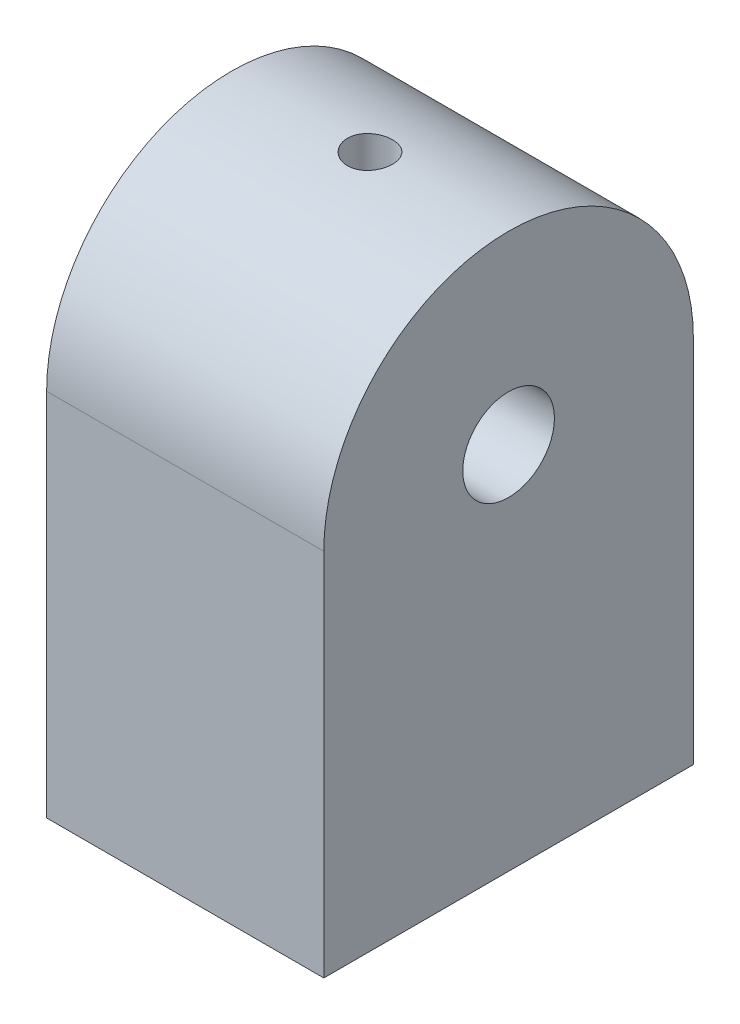
SolidWorks part; units mm, degrees
ref_plane "Front Plane" through (0, 0, 0) normal (0, 0, 1) x (1, 0, 0)
ref_plane "Top Plane" through (0, 0, 0) normal (0, 1, 0) x (1, 0, 0)
ref_plane "Right Plane" through (0, 0, 0) normal (1, 0, 0) x (0, 0, -1)
sketch "Sketch1" plane through (0, 0, 0) normal (1, 0, 0) x (0, 0, -1)
  circle A0 centre (0, 0) radius 3.15
  circle A1 centre (0, 0) radius 12.7
  point P5 (0, 0.2014)
  dimension "D1" = 6.3
  dimension "D2" = 25.4
extrude "Boss-Extrude1" add sketch "Sketch1" along normal blind 19.05
sketch "Sketch2" plane through (19.05, 0, 0) normal (1, 0, 0) x (0, 0, -1)
  line L0 (12.7, 0) -> (12.7, -25.4)
  line L1 (-12.7, 0) -> (-12.7, -25.4)
  line L2 (12.7, -25.4) -> (-12.7, -25.4)
  circle A0 centre (0, 0) radius 12.7 construction
  circle A1 centre (0, 0) radius 12.7
  circle A2 centre (0, 0) radius 12.7
  circle M4 centre (0, 0) radius 12.7
  dimension "D2" = 25.4
  dimension "D1" = 0
extrude "Boss-Extrude2" add sketch "Sketch2" against normal up to surface (19.05 mm away) contours L0 L2 L1 M4 up to face at (0, 0, -12.7)
ref_plane "Plane1" through (0, 12.7, 0) normal (0, 1, 0) x (1, 0, 0)
sketch "Sketch3" plane through (0, 12.7, 0) normal (0, 1, 0) x (1, 0, 0)
  line L0 (0, 12.7) -> (0, -12.7) construction
  line L1 (0, 12.7) -> (0, -12.7)
  line L2 (19.05, -12.7) -> (19.05, 12.7) construction
  line L3 (19.05, -12.7) -> (19.05, 12.7)
  line L4 (0, 12.7) -> (19.05, 12.7) construction
  line L5 (0, 12.7) -> (19.05, 12.7)
  line L6 (0, -12.7) -> (19.05, -12.7) construction
  line L7 (0, -12.7) -> (19.05, -12.7)
  circle A0 centre (9.525, 0) radius 1.55
  dimension "D1" = 3.1
extrude "Cut-Extrude1" cut sketch "Sketch3" against normal up to surface (9.9577 mm away) contours A0
